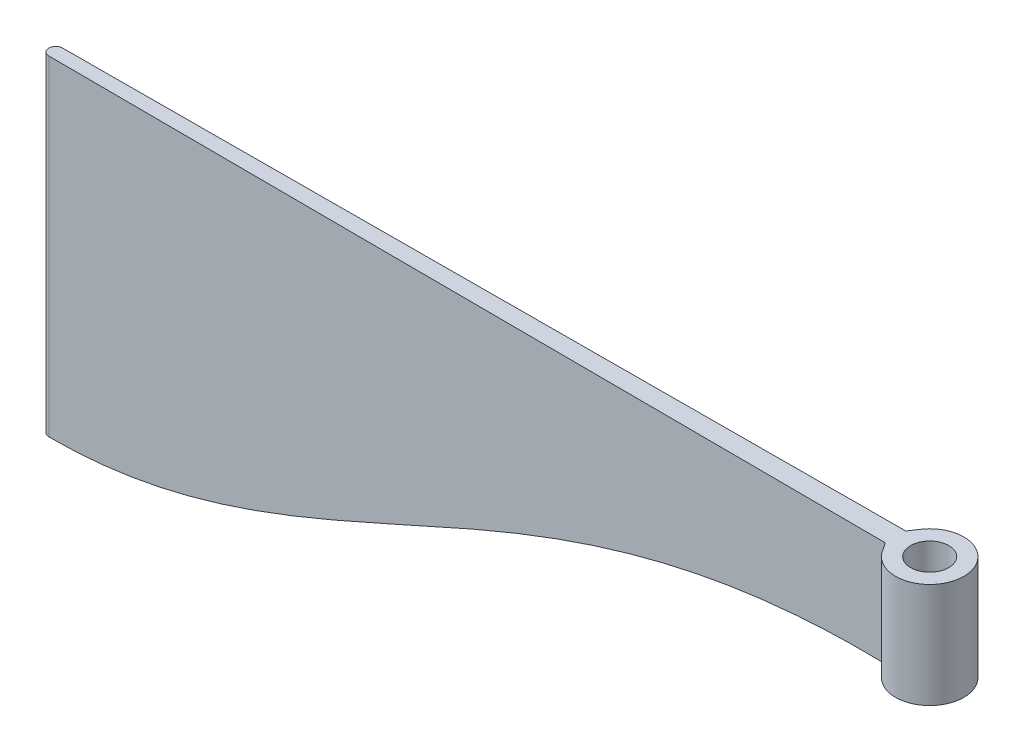
SolidWorks part; units mm, degrees
ref_plane "Ön Düzlem" through (0, 0, 0) normal (0, 0, 1) x (1, 0, 0)
ref_plane "Üst Düzlem" through (0, 0, 0) normal (0, 1, 0) x (1, 0, 0)
ref_plane "Sağ Düzlem" through (0, 0, 0) normal (1, 0, 0) x (0, 0, -1)
sketch "Çizim1" plane through (0, 0, 0) normal (0, 0, 1) x (1, 0, 0)
  line L0 (51.7442, 14.308) -> (56.8957, 14.308)
  line L1 (56.8957, 14.308) -> (56.8957, 29.6603)
  line L2 (56.8957, 29.6603) -> (-67.0322, 29.6603)
  line L3 (-67.0322, 29.6603) -> (-67.0322, -18.6201)
  spline S0 degree 3 poles (51.7442, 14.308) (32.353, 13.9421) (-5.5355, 3.0293) (-42.7613, -18.9941) (-67.0322, -18.6201) knots 0 0 0 0 0.428556 1 1 1 1
extrude "Yükseklik-Ekstrüzyon1" add sketch "Çizim1" along normal blind 3
sketch "Çizim2" plane through (0, 29.6603, 0) normal (0, 1, 0) x (1, 0, 0)
  line L4 (56.8957, 0) -> (-67.0322, 0)
  line L5 (-67.0322, 0) -> (-67.0322, -3)
  line L6 (-67.0322, -3) -> (56.8957, -3)
  line L7 (56.8957, -3) -> (56.8957, 0)
  line L8 (56.8957, 0) -> (-67.0322, 0)
  line L9 (-67.0322, 0) -> (-67.0322, -3)
  line L10 (-67.0322, -3) -> (56.8957, -3)
  line L11 (56.8957, -3) -> (56.8957, 0)
  dimension "D1" = 0
sketch "Çizim5" plane through (0, 29.6603, 0) normal (0, 1, 0) x (1, 0, 0)
  line L0 (56.8957, 0) -> (57.9189, 1.5307)
  line L2 (56.8957, 0) -> (56.8957, -3)
  line L4 (56.8957, 0) -> (56.8957, -3)
  line L6 (56.8957, -3) -> (57.9189, -4.5307)
  arc A0 (57.5749, -4.016) -> (57.5749, 1.016) centre (61.8957, -1.5) ccw
  line M4 (56.8957, -3) -> (56.8957, 0)
extrude "Yükseklik-Ekstrüzyon3" add sketch "Çizim5" against normal up to surface (15.3522 mm away) contours L6 A0 L0 M4 up to face at (54.32, 14.308, 1.5)
sketch "Çizim7" plane through (0, 29.6603, 0) normal (0, 1, 0) x (1, 0, 0)
  line L1 (56.8957, 0) -> (56.8957, -3)
  line L2 (-67.0322, -2.5) -> (56.8957, -3)
  line L4 (-67.0322, -0.5) -> (56.8957, 0)
  line L5 (56.8957, 0) -> (-67.0322, 0)
  line L6 (-67.0322, 0) -> (-67.0322, -3)
  line L7 (-67.0322, -3) -> (56.8957, -3)
  line L8 (56.8957, -3) -> (57.9189, -4.5307)
  line L9 (57.9189, 1.5307) -> (56.8957, 0)
  line L10 (56.8957, 0) -> (-67.0322, 0)
  line L11 (-67.0322, 0) -> (-67.0322, -3)
  line L12 (-67.0322, -3) -> (56.8957, -3)
  line L13 (56.8957, -3) -> (57.9189, -4.5307)
  line L14 (57.9189, 1.5307) -> (56.8957, 0)
  line L15 (-67.0322, -0.5) -> (-67.0322, -2.5)
  arc A1 (57.9189, -4.5307) -> (57.9189, 1.5307) centre (61.8957, -1.5) ccw
  arc A2 (57.9189, -4.5307) -> (57.9189, 1.5307) centre (61.8957, -1.5) ccw
  line M7 (56.8957, 0) -> (-67.0322, 0)
  line M8 (-67.0322, 0) -> (-67.0322, -3)
  line M9 (-67.0322, -3) -> (56.8957, -3)
  dimension "D2" = 0.5
  dimension "D1" = 0
extrude "Kes-Ekstrüzyon6" cut sketch "Çizim7" against normal through all contours L4 M8 M7 | L2 M8 M9
fillet "Radyus1" radius 1 2 edges at (-67.0322, 5.5201, 2.5) (-67.0322, 5.5201, 0.5)
sketch "Çizim9" plane through (0, 29.6603, 0) normal (0, 1, 0) x (-1, 0, 0)
  line L0 (-56.8957, 3) -> (-57.9189, 4.5307) construction
  line L1 (-56.8957, 3) -> (-57.9189, 4.5307)
  line L7 (67.0322, 1.496) -> (67.0322, 1.504)
  line L8 (66.0362, 2.504) -> (-56.8957, 3)
  line L9 (-56.8957, 3) -> (-57.9189, 4.5307)
  line L10 (-57.9189, -1.5307) -> (-56.8957, 0)
  line L11 (-56.8957, 0) -> (66.0362, 0.496)
  line L12 (67.0322, 1.496) -> (67.0322, 1.504)
  line L13 (66.0362, 2.504) -> (-56.8957, 3)
  line L14 (-56.8957, 3) -> (-57.9189, 4.5307)
  line L15 (-57.9189, -1.5307) -> (-56.8957, 0)
  line L16 (-56.8957, 0) -> (66.0362, 0.496)
  arc A0 (-57.9189, 4.5307) -> (-57.9189, -1.5307) centre (-61.8957, 1.5) ccw construction
  arc A1 (-57.9189, 4.5307) -> (-57.9189, -1.5307) centre (-61.8957, 1.5) ccw
  circle A2 centre (-61.8957, 1.5) radius 2.8
  arc A5 (67.0322, 1.504) -> (66.0362, 2.504) centre (66.0322, 1.504) ccw
  arc A6 (-57.9189, 4.5307) -> (-57.9189, -1.5307) centre (-61.8957, 1.5) ccw
  arc A7 (66.0362, 0.496) -> (67.0322, 1.496) centre (66.0322, 1.496) ccw
  arc A8 (67.0322, 1.504) -> (66.0362, 2.504) centre (66.0322, 1.504) ccw
  arc A9 (-57.9189, 4.5307) -> (-57.9189, -1.5307) centre (-61.8957, 1.5) ccw
  arc A10 (66.0362, 0.496) -> (67.0322, 1.496) centre (66.0322, 1.496) ccw
  dimension "D2" = 5.6
  dimension "D1" = 0
extrude "Kes-Ekstrüzyon7" cut sketch "Çizim9" against normal blind 13 contours A2
